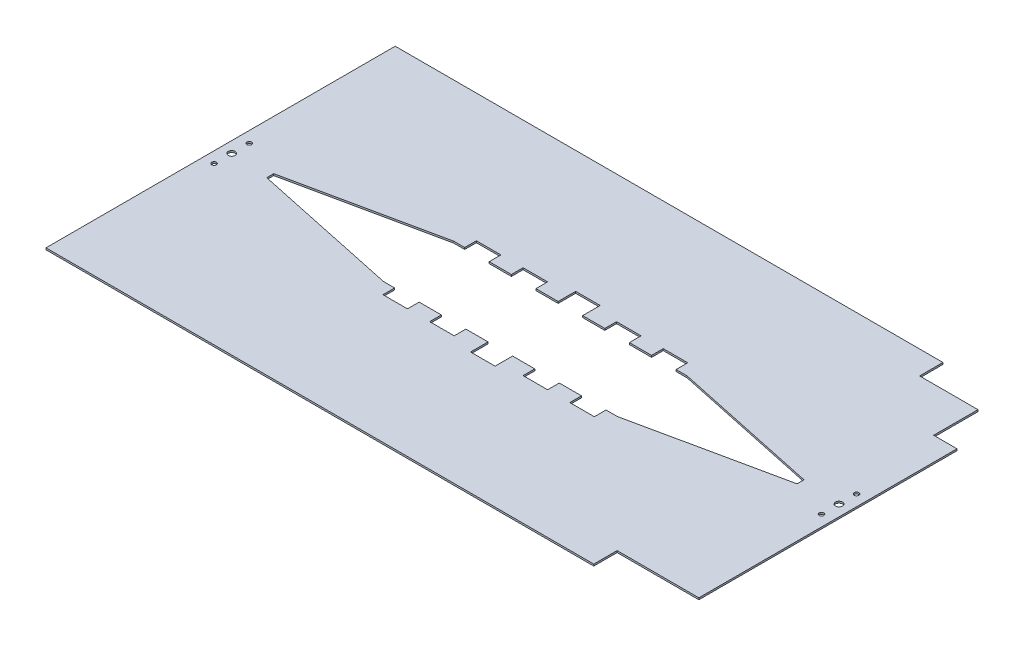
SolidWorks part; units mm, degrees
ref_plane "Front Plane" through (0, 0, 0) normal (0, 0, 1) x (1, 0, 0)
ref_plane "Top Plane" through (0, 0, 0) normal (0, 1, 0) x (1, 0, 0)
ref_plane "Right Plane" through (0, 0, 0) normal (1, 0, 0) x (0, 0, -1)
sketch "Sketch1" plane through (0, 0, 0) normal (0, 1, 0) x (1, 0, 0)
  line L1 (269.5, -149.5) -> (-269.5, -149.5)
  line L2 (269.5, -149.5) -> (269.5, 149.5)
  line L3 (269.5, 149.5) -> (-269.5, 149.5)
  line L4 (-269.5, -149.5) -> (-269.5, 149.5)
  line L5 (269.5, -149.5) -> (-269.5, 149.5) construction
  line L6 (269.5, 149.5) -> (-269.5, -149.5) construction
  point P0 (0, 0)
  dimension "D1" = 299
  dimension "D2" = 539
extrude "Boss-Extrude1" add sketch "Sketch1" against normal blind 1.5
sketch "Sketch10" plane through (0, 0, 0) normal (0, 1, 0) x (1, 0, 0)
  line L0 (269.5, 149.5) -> (199.5, 149.5)
  line L1 (269.5, -149.5) -> (199.5, -149.5)
  line L2 (269.5, -149.5) -> (269.5, -129.5)
  line L3 (269.5, -129.5) -> (199.5, -129.5)
  line L4 (199.5, -149.5) -> (199.5, -129.5)
  line L5 (269.5, 149.5) -> (-269.5, 149.5) construction
  line L6 (199.5, 149.5) -> (199.5, 129.5)
  line L7 (199.5, 129.5) -> (249.5, 129.5)
  line L8 (249.5, 129.5) -> (249.5, 91.5)
  line L9 (249.5, 91.5) -> (269.5, 91.5)
  line L10 (269.5, -149.5) -> (269.5, 149.5) construction
  line L11 (269.5, 91.5) -> (269.5, 149.5)
  dimension "D1" = 70
  dimension "D2" = 20
  dimension "D3" = 20
  dimension "D4" = 70
  dimension "D5" = 20
  dimension "D6" = 58
extrude "Cut-Extrude6" cut sketch "Sketch10" against normal through all
sketch "Sketch2" plane through (0, 0, 0) normal (0, 1, 0) x (1, 0, 0)
  line L0 (-269.5, 0) -> (-260, 0) construction
  line L1 (-269.5, 149.5) -> (-269.5, -149.5) construction
  line L2 (-260, 0) -> (-260, 15) construction
  line L3 (-260, 0) -> (-260, -15) construction
  line L4 (-260, -15) -> (-260, 15) construction
  circle A0 centre (-260, 0) radius 3
  circle A1 centre (-260, 15) radius 2
  circle A2 centre (-260, -15) radius 2
  dimension "D1" = 6
  dimension "D5" = 4
  dimension "D2" = 9.5
  dimension "D3" = 15
  dimension "D4" = 15
extrude "Cut-Extrude1" cut sketch "Sketch2" against normal blind 10
mirror "Mirror1" about plane through (0, 0, 0) normal (1, 0, 0) of "Cut-Extrude1"
sketch "Sketch11" plane through (0, 0, 0) normal (0, 1, 0) x (1, 0, 0)
  line L10 (199.5, -149.5) -> (199.5, -129.5)
  line L11 (199.5, -129.5) -> (269.5, -129.5)
  line L12 (269.5, -129.5) -> (269.5, 91.5)
  line L13 (269.5, 91.5) -> (249.5, 91.5)
  line L14 (249.5, 91.5) -> (249.5, 129.5)
  line L15 (249.5, 129.5) -> (199.5, 129.5)
  line L16 (199.5, 129.5) -> (199.5, 149.5)
  line L17 (199.5, 149.5) -> (-269.5, 149.5)
  line L18 (-269.5, 149.5) -> (-269.5, -149.5)
  line L19 (-269.5, -149.5) -> (199.5, -149.5)
  line L20 (199.5, -149.5) -> (199.5, -129.5)
  line L21 (199.5, -129.5) -> (269.5, -129.5)
  line L22 (269.5, -129.5) -> (269.5, 91.5)
  line L23 (269.5, 91.5) -> (249.5, 91.5)
  line L24 (249.5, 91.5) -> (249.5, 129.5)
  line L25 (249.5, 129.5) -> (199.5, 129.5)
  line L26 (199.5, 129.5) -> (199.5, 149.5)
  line L27 (199.5, 149.5) -> (-269.5, 149.5)
  line L28 (-269.5, 149.5) -> (-269.5, -149.5)
  line L29 (-269.5, -149.5) -> (199.5, -149.5)
  line L70 (-90.5, -40) -> (-69.5, -40)
  line L71 (-90.5, -30) -> (-90.5, -40)
  line L72 (-100, -30) -> (-90.5, -30)
  line L73 (-227.025, -3) -> (-100, -30)
  line L74 (-260, -3) -> (-227.025, -3)
  line L75 (-227.025, 3) -> (-260, 3)
  line L76 (-100, 30) -> (-227.025, 3)
  line L77 (-90.5, 30) -> (-100, 30)
  line L78 (-90.5, 40) -> (-90.5, 30)
  line L79 (-69.5, 40) -> (-90.5, 40)
  line L80 (-69.5, 30) -> (-69.5, 40)
  line L81 (-50.5, 30) -> (-69.5, 30)
  line L82 (-50.5, 40) -> (-50.5, 30)
  line L83 (-29.5, 40) -> (-50.5, 40)
  line L84 (-29.5, 30) -> (-29.5, 40)
  line L85 (-10.5, 30) -> (-29.5, 30)
  line L86 (-10.5, 45) -> (-10.5, 30)
  line L87 (10.5, 45) -> (-10.5, 45)
  line L88 (10.5, 30) -> (10.5, 45)
  line L89 (29.5, 30) -> (10.5, 30)
  line L90 (29.5, 40) -> (29.5, 30)
  line L91 (50.5, 40) -> (29.5, 40)
  line L92 (50.5, 30) -> (50.5, 40)
  line L93 (69.5, 30) -> (50.5, 30)
  line L94 (69.5, 40) -> (69.5, 30)
  line L95 (90.5, 40) -> (69.5, 40)
  line L96 (90.5, 30) -> (90.5, 40)
  line L97 (100, 30) -> (90.5, 30)
  line L98 (90.5, -30) -> (100, -30)
  line L99 (260, 3) -> (227.025, 3)
  line L100 (90.5, -30) -> (100, -30)
  line L101 (100, -30) -> (227.025, -3)
  line L102 (100, -30) -> (227.025, -3)
  line L103 (90.5, -40) -> (90.5, -30)
  line L104 (69.5, -40) -> (90.5, -40)
  line L105 (69.5, -30) -> (69.5, -40)
  line L106 (50.5, -30) -> (69.5, -30)
  line L107 (50.5, -40) -> (50.5, -30)
  line L108 (29.5, -40) -> (50.5, -40)
  line L109 (29.5, -30) -> (29.5, -40)
  line L110 (10.5, -30) -> (29.5, -30)
  line L111 (10.5, -45) -> (10.5, -30)
  line L112 (-10.5, -45) -> (10.5, -45)
  line L113 (-10.5, -30) -> (-10.5, -45)
  line L114 (-29.5, -30) -> (-10.5, -30)
  line L115 (-29.5, -40) -> (-29.5, -30)
  line L116 (-50.5, -40) -> (-29.5, -40)
  line L117 (-50.5, -30) -> (-50.5, -40)
  line L118 (-69.5, -30) -> (-50.5, -30)
  line L119 (-69.5, -40) -> (-69.5, -30)
  line L120 (-90.5, -40) -> (-69.5, -40)
  line L121 (-90.5, -30) -> (-90.5, -40)
  line L122 (-100, -30) -> (-90.5, -30)
  line L123 (-227.025, -3) -> (-100, -30)
  line L124 (-260, -3) -> (-227.025, -3) construction
  line L125 (-227.025, 3) -> (-260, 3) construction
  line L126 (-100, 30) -> (-227.025, 3)
  line L127 (-90.5, 30) -> (-100, 30)
  line L128 (-90.5, 40) -> (-90.5, 30)
  line L129 (-69.5, 40) -> (-90.5, 40)
  line L130 (-69.5, 30) -> (-69.5, 40)
  line L131 (-50.5, 30) -> (-69.5, 30)
  line L132 (-50.5, 40) -> (-50.5, 30)
  line L133 (-29.5, 40) -> (-50.5, 40)
  line L134 (-29.5, 30) -> (-29.5, 40)
  line L135 (-10.5, 30) -> (-29.5, 30)
  line L136 (-10.5, 45) -> (-10.5, 30)
  line L137 (10.5, 45) -> (-10.5, 45)
  line L138 (10.5, 30) -> (10.5, 45)
  line L139 (29.5, 30) -> (10.5, 30)
  line L140 (29.5, 40) -> (29.5, 30)
  line L141 (50.5, 40) -> (29.5, 40)
  line L142 (50.5, 30) -> (50.5, 40)
  line L143 (69.5, 30) -> (50.5, 30)
  line L144 (69.5, 40) -> (69.5, 30)
  line L145 (90.5, 40) -> (69.5, 40)
  line L146 (90.5, 30) -> (90.5, 40)
  line L147 (100, 30) -> (90.5, 30)
  line L149 (260, 3) -> (227.025, 3) construction
  line L153 (90.5, -40) -> (90.5, -30)
  line L154 (69.5, -40) -> (90.5, -40)
  line L155 (69.5, -30) -> (69.5, -40)
  line L156 (50.5, -30) -> (69.5, -30)
  line L157 (50.5, -40) -> (50.5, -30)
  line L158 (29.5, -40) -> (50.5, -40)
  line L159 (29.5, -30) -> (29.5, -40)
  line L160 (10.5, -30) -> (29.5, -30)
  line L161 (10.5, -45) -> (10.5, -30)
  line L162 (-10.5, -45) -> (10.5, -45)
  line L163 (-10.5, -30) -> (-10.5, -45)
  line L164 (-29.5, -30) -> (-10.5, -30)
  line L165 (-29.5, -40) -> (-29.5, -30)
  line L166 (-50.5, -40) -> (-29.5, -40)
  line L167 (-50.5, -30) -> (-50.5, -40)
  line L168 (-69.5, -30) -> (-50.5, -30)
  line L169 (-69.5, -40) -> (-69.5, -30)
  line L170 (-227.025, 3) -> (-227.025, -3)
  line L171 (227.025, 3) -> (227.025, -3)
  line L422 (227.025, -3) -> (260, -3)
  line L423 (227.025, -3) -> (260, -3)
  line L424 (227.025, 3) -> (100, 30)
  line L425 (227.025, 3) -> (100, 30)
  arc A2 (-260, 3) -> (-260, -3) centre (-260, 0) ccw
  arc A3 (260, -3) -> (260, 3) centre (260, 0) ccw
  arc A4 (-260, 3) -> (-260, -3) centre (-260, 0) ccw construction
  arc A5 (260, -3) -> (260, 3) centre (260, 0) ccw construction
  dimension "D1" = 0
  dimension "D2" = 0
extrude "Cut-Extrude7" cut sketch "Sketch11" against normal through all contours L171 L425 L147 L146 L145 L144 L143 L142 L141 L140 L139 L138 L137 L136 L135 L134 L133 L132 L131 L130 L129 L128 L127 L126 L170 L123 L122 L121 L120 L169 L168 L167 L166 L165 L164 L163 L162 L161 L160 L159 L158 L157 L156 L155 L154 L153 L100 L102
equation "\"D9@Sketch7\"=\"D1@Sketch7\""
equation "\"D8@Sketch7\"=\"D1@Sketch7\""
equation "\"D7@Sketch7\"=\"D1@Sketch7\""
equation "\"D6@Sketch7\"=\"D1@Sketch7\""
equation "\"D5@Sketch7\"=\"D1@Sketch7\""
equation "\"D4@Sketch7\"=\"D1@Sketch7\""
equation "\"D3@Sketch7\"=\"D1@Sketch7\""
equation "\"D31@Sketch7\"=\"D1@Sketch7\""
equation "\"D2@Sketch7\"=\"D1@Sketch7\""
equation "\"D29@Sketch7\"=\"D1@Sketch7\""
equation "\"D28@Sketch7\"=\"D1@Sketch7\""
equation "\"D25@Sketch7\"=\"D1@Sketch7\""
equation "\"D24@Sketch7\"=\"D1@Sketch7\""
equation "\"D23@Sketch7\"=\"D1@Sketch7\""
equation "\"D22@Sketch7\"=\"D1@Sketch7\""
equation "\"D20@Sketch7\"=\"D1@Sketch7\""
equation "\"D19@Sketch7\"=\"D1@Sketch7\""
equation "\"D18@Sketch7\"=\"D1@Sketch7\""
equation "\"D17@Sketch7\"=\"D1@Sketch7\""
equation "\"D16@Sketch7\"=\"D1@Sketch7\""
equation "\"D14@Sketch7\"=\"D1@Sketch7\""
equation "\"D13@Sketch7\"=\"D1@Sketch7\""
equation "\"D12@Sketch7\"=\"D1@Sketch7\""
equation "\"D11@Sketch7\"=\"D1@Sketch7\""
